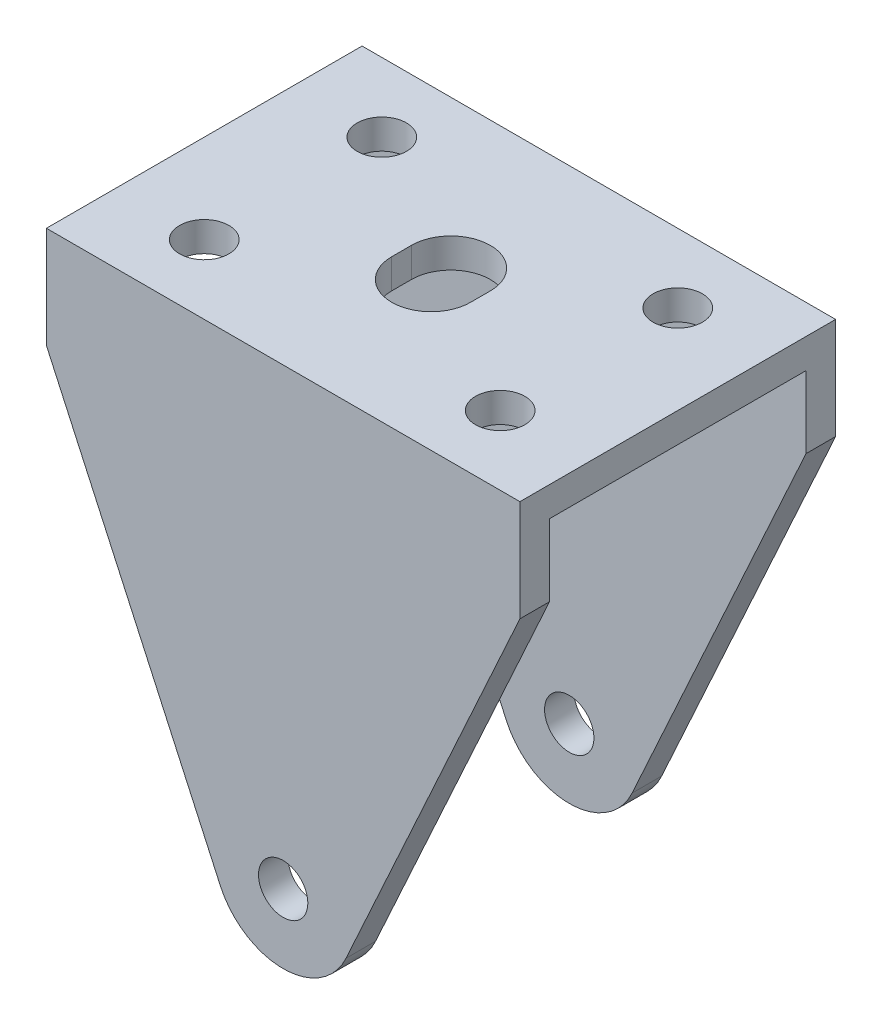
SolidWorks part; units mm, degrees
ref_plane "Front Plane" through (0, 0, 0) normal (0, 0, 1) x (1, 0, 0)
ref_plane "Top Plane" through (0, 0, 0) normal (0, 1, 0) x (1, 0, 0)
ref_plane "Right Plane" through (0, 0, 0) normal (1, 0, 0) x (0, 0, -1)
sketch "Sketch1" plane through (0, 0, 0) normal (0, 1, 0) x (1, 0, 0)
  line L1 (24, -16) -> (-24, -16)
  line L2 (24, -16) -> (24, 16)
  line L3 (24, 16) -> (-24, 16)
  line L4 (-24, -16) -> (-24, 16)
  line L5 (24, -16) -> (-24, 16) construction
  line L6 (24, 16) -> (-24, -16) construction
  point P0 (0, 0)
  dimension "D1" = 32
  dimension "D2" = 48
extrude "Boss-Extrude1" add sketch "Sketch1" against normal blind 3
sketch "Sketch2" plane through (0, -3, 0) normal (0, -1, 0) x (1, 0, 0)
  line L0 (24, 16) -> (24, -16) construction
  line L1 (-24, 16) -> (24, 16)
  line L2 (-24, 16) -> (-24, 13)
  line L3 (-24, 13) -> (24, 13)
  line L4 (24, 16) -> (24, 13)
  line L5 (-24, 0) -> (24, 0) construction
  line L6 (-24, -16) -> (-24, 16) construction
  line L7 (24, -16) -> (24, -13)
  line L8 (-24, -13) -> (24, -13)
  line L9 (-24, -16) -> (-24, -13)
  line L10 (-24, -16) -> (24, -16)
  dimension "D1" = 3
extrude "Boss-Extrude2" add sketch "Sketch2" along normal blind 50
sketch "Sketch3" plane through (0, 0, 16) normal (0, 0, 1) x (1, 0, 0)
  line L0 (24, -10.2872) -> (6.3677, -48.9072)
  line L1 (24, -53) -> (24, 0) construction
  line L2 (0, -46) -> (0, 0) construction
  line L3 (24, -53) -> (-24, -53) construction
  line L4 (-24, -10.2872) -> (-6.3677, -48.9072)
  line L5 (24, -10.2872) -> (24, -53)
  line L6 (24, -53) -> (-24, -53)
  line L7 (-24, -53) -> (-24, -10.2872)
  circle A0 centre (0, -46) radius 7
  circle A1 centre (0, -46) radius 2.5
  dimension "D1" = 14
  dimension "D2" = 5
extrude "Cut-Extrude1" cut sketch "Sketch3" against normal through all both and the other way through all
sketch "Sketch4" plane through (0, 0, 0) normal (0, 1, 0) x (1, 0, 0)
  point P0 (-15, 9)
  point P1 (15, 9)
  point P3 (15, -9)
  point P5 (-15, -9)
hole_wizard "Ø5.0 (5) Diameter Hole1" positions "Sketch5" profile "Sketch6" hole size "Ø5.0" standard "ISO" end condition through all
sketch "Sketch5" plane through (0, 0, 0) normal (0, 1, 0) x (1, 0, 0)
  point P0 (-15, -9)
  point P3 (-15, 9)
  point P6 (15, 9)
  point P9 (15, -9)
sketch "Sketch6" plane through (-15, 0, 9) normal (1, 0, 0) x (0, 0, 1)
  line L0 (0, 0) -> (0, 53)
  line L1 (0, 53) -> (2.5, 53)
  line L2 (2.5, 53) -> (2.5, 0)
  line L5 (2.5, 0) -> (0, 0)
  line L11 (0, -6.35) -> (0, 107.95) construction
  dimension "Thru Hole Dia." = 5
  dimension "Thru Hole Depth" = 53
sketch "Çizim1" plane through (0, 0, 0) normal (0, 1, 0) x (1, 0, 0)
  line L0 (-4, 1) -> (-4, -1)
  line L1 (4, 1) -> (4, -1)
  line L2 (0, 0) -> (0.7986, 0) construction
  arc A0 (4, 1) -> (-4, 1) centre (0, 1) ccw
  arc A1 (4, -1) -> (-4, -1) centre (0, -1) cw
  point P7 (0, 0)
  point P10 (-4, 0)
  point P11 (4, 0)
  dimension "D2" = 4
  dimension "D1" = 1
extrude "Kes-Ekstrüzyon1" cut sketch "Çizim1" against normal blind 7
